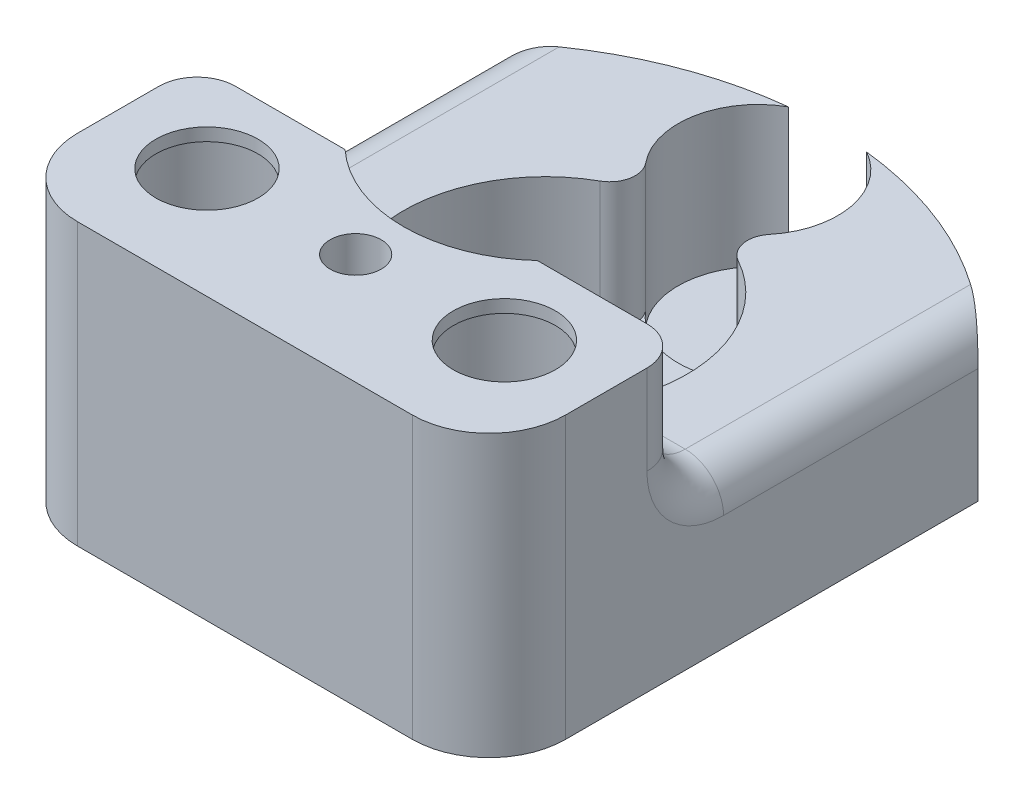
SolidWorks part; units mm, degrees
ref_plane "Front Plane" through (0, 0, 0) normal (0, 0, 1) x (1, 0, 0)
ref_plane "Top Plane" through (0, 0, 0) normal (0, 1, 0) x (1, 0, 0)
ref_plane "Right Plane" through (0, 0, 0) normal (1, 0, 0) x (0, 0, -1)
sketch "Sketch1" plane through (0, 0, 0) normal (0, 1, 0) x (1, 0, 0)
  circle A0 centre (0, 0) radius 34.445
  dimension "D1" = 68.89
extrude "Boss-Extrude1" add sketch "Sketch1" along normal blind 22
sketch "Sketch5" plane through (0, 22, 0) normal (0, 1, 0) x (1, 0, 0)
  line L0 (0, 34.445) -> (0, -34.445) construction
  circle A0 centre (0, 0) radius 34.445 construction
sketch "Sketch15" plane through (0, 22, 0) normal (0, 1, 0) x (1, 0, 0)
  line L1 (-19.1096, 20.6169) -> (-19.1096, -17.6787)
  line L3 (0, 34.445) -> (0, -34.445) construction
  line L4 (-19.1096, -17.6787) -> (19.1096, -17.6787)
  line L5 (0, -17.6787) -> (0, -34.445)
  line L6 (0, 34.445) -> (0, -34.445) construction
  line L7 (19.1096, 20.6169) -> (19.1096, -17.6787)
  arc A1 (-19.1096, 20.6169) -> (19.1096, 20.6169) centre (0, 0) cw
  circle A3 centre (0, 0) radius 34.445
extrude "Cut-Extrude2" cut sketch "Sketch15" against normal through all contours L6 A1 L1 L4 | A1 L6 L4 L7 | A3
sketch "Sketch17" plane through (0, 22, 0) normal (0, 1, 0) x (1, 0, 0)
  line L0 (-19.1096, 1.4691) -> (19.1096, 1.4691) construction
  line L1 (-19.1096, 20.6169) -> (-19.1096, -17.6787) construction
  line L2 (19.1096, 20.6169) -> (19.1096, -17.6787) construction
  line L3 (-11.6441, -9.0085) -> (11.6441, -9.0085)
  circle A0 centre (-11.6441, -9.0085) radius 6.2
  circle A2 centre (11.6441, -9.0085) radius 6.2
extrude "Cut-Extrude4" cut sketch "Sketch17" against normal blind 20 from offset 1 contours A0 | A2 offset against normal yes
sketch "Sketch18" plane through (0, 22, 0) normal (0, 1, 0) x (1, 0, 0)
  line L0 (0, 34.445) -> (0, -34.445) construction
  circle A0 centre (0, 5.8463) radius 7.25
  dimension "D1" = 14.5
extrude "Cut-Extrude5" cut sketch "Sketch18" against normal through all
sketch "Sketch19" plane through (0, 22, 0) normal (0, 1, 0) x (1, 0, 0)
  line L0 (0, 34.445) -> (0, -34.445) construction
  circle A0 centre (0, 22.4979) radius 6.25
  dimension "D1" = 12.5
extrude "Cut-Extrude7" cut sketch "Sketch19" against normal blind 21 contours A0
sketch "Sketch20" plane through (0, 22, 0) normal (0, 1, 0) x (1, 0, 0)
  circle A0 centre (0, 5.8463) radius 9.846
extrude "Cut-Extrude9" cut sketch "Sketch20" against normal blind 10
fillet "Fillet12" radius 6 2 edges at (-19.1096, 11, 17.6787) (19.1096, 11, 17.6787)
sketch "Sketch23" plane through (0, 22, 0) normal (0, 1, 0) x (1, 0, 0)
  line L0 (0, 34.445) -> (0, -34.445) construction
  circle A0 centre (-11.6441, -9.0085) radius 4
  circle A1 centre (11.6441, -9.0085) radius 4
  circle A2 centre (0, -9.0085) radius 2
  dimension "D1" = 2
extrude "Cut-Extrude10" cut sketch "Sketch23" against normal through all
sketch "Sketch24" plane through (0, 0, 0) normal (0, -1, 0) x (1, 0, 0)
  line L0 (19.1096, -20.6169) -> (19.1096, 11.6787) construction
  line L2 (-19.1096, -20.6169) -> (-19.1096, 2.3098)
  line L3 (-19.1096, 2.3098) -> (19.1096, 2.3098)
  line L4 (19.1096, -20.6169) -> (19.1096, 2.3098)
  arc A0 (-19.1096, -20.6169) -> (19.1096, -20.6169) centre (0, 0) ccw
  arc A1 (-19.1096, -20.6169) -> (19.1096, -20.6169) centre (0, 0) ccw construction
extrude "Cut-Extrude11" cut sketch "Sketch24" against normal through all from offset 12 offset against normal yes
fillet "Fillet19" radius 3 6 edges at (-19.1096, 17, 2.3098) (19.1096, 17, 2.3098) (-19.1096, 12, -9.1536) (19.1096, 12, -9.1536) (12.3126, 12, 2.3098) (-12.3126, 12, 2.3098)
sketch "Sketch25" plane through (0, 12, 0) normal (0, 1, 0) x (1, 0, 0)
  circle A0 centre (0, 5.8463) radius 11.1
  dimension "D1" = 22.2
extrude "Cut-Extrude12" cut sketch "Sketch25" against normal blind 10 and the other way blind 10
fillet "Fillet20" radius 2 2 edges at (2.3308, 7, -16.6988) (-2.3308, 7, -16.6988)
